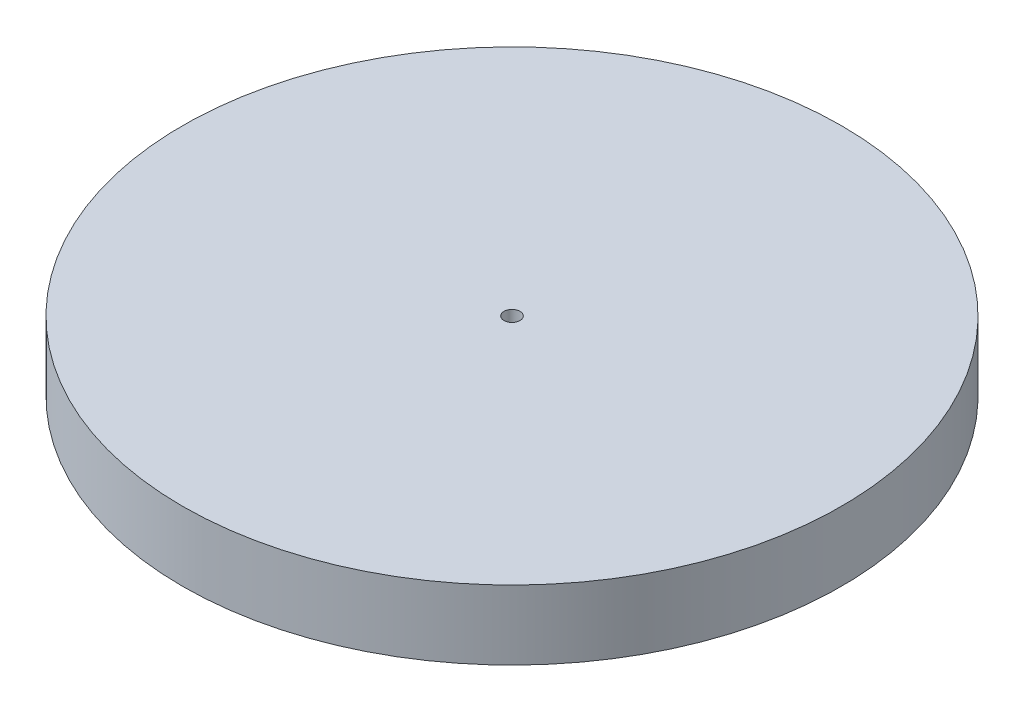
SolidWorks part; units mm, degrees
ref_plane "Front Plane" through (0, 0, 0) normal (0, 0, 1) x (1, 0, 0)
ref_plane "Top Plane" through (0, 0, 0) normal (0, 1, 0) x (1, 0, 0)
ref_plane "Right Plane" through (0, 0, 0) normal (1, 0, 0) x (0, 0, -1)
sketch "Sketch1" plane through (0, 0, 0) normal (0, 1, 0) x (1, 0, 0)
  circle A0 centre (0, 0) radius 43.25
  circle A1 centre (0, 0) radius 1.05
  dimension "D1" = 2.1
  dimension "D2" = 86.5
extrude "Boss-Extrude1" add sketch "Sketch1" along normal blind 9.1
